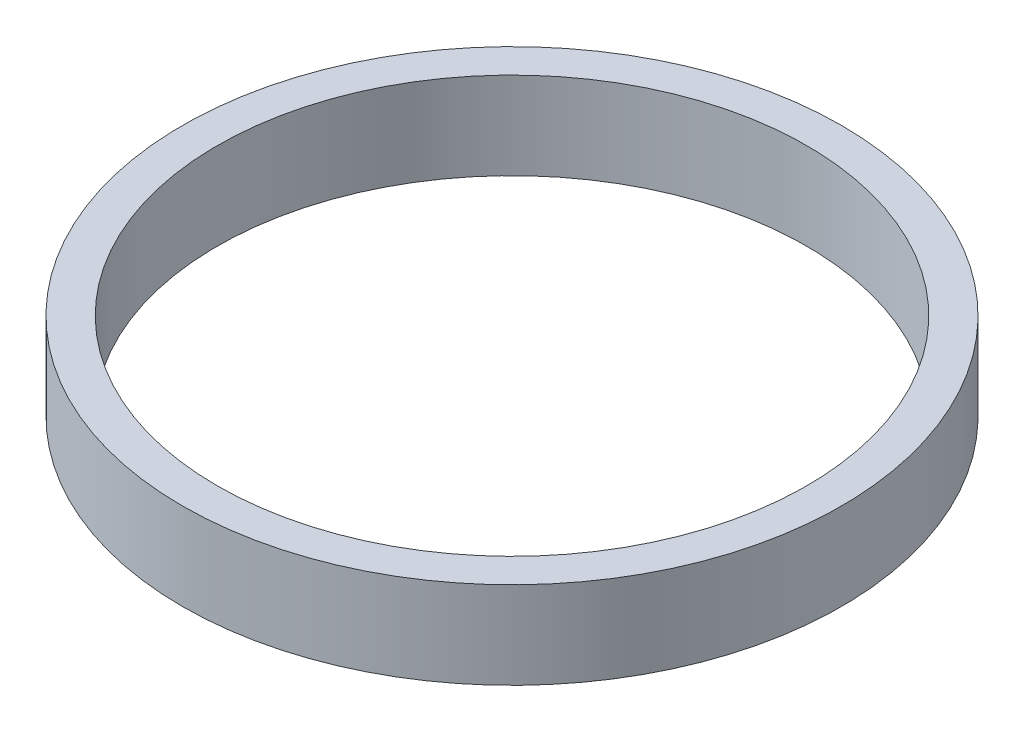
SolidWorks part; units mm, degrees
ref_plane "前视基准面" through (0, 0, 0) normal (0, 0, 1) x (1, 0, 0)
ref_plane "上视基准面" through (0, 0, 0) normal (0, 1, 0) x (1, 0, 0)
ref_plane "右视基准面" through (0, 0, 0) normal (1, 0, 0) x (0, 0, -1)
sketch "草图1" plane through (0, 0, 0) normal (0, 1, 0) x (1, 0, 0)
  circle A0 centre (0, 0) radius 11.35
  circle A1 centre (0, 0) radius 10.15
  dimension "D1" = 20.3
  dimension "D2" = 1.2
extrude "凸台-拉伸1" add sketch "草图1" along normal blind 3
